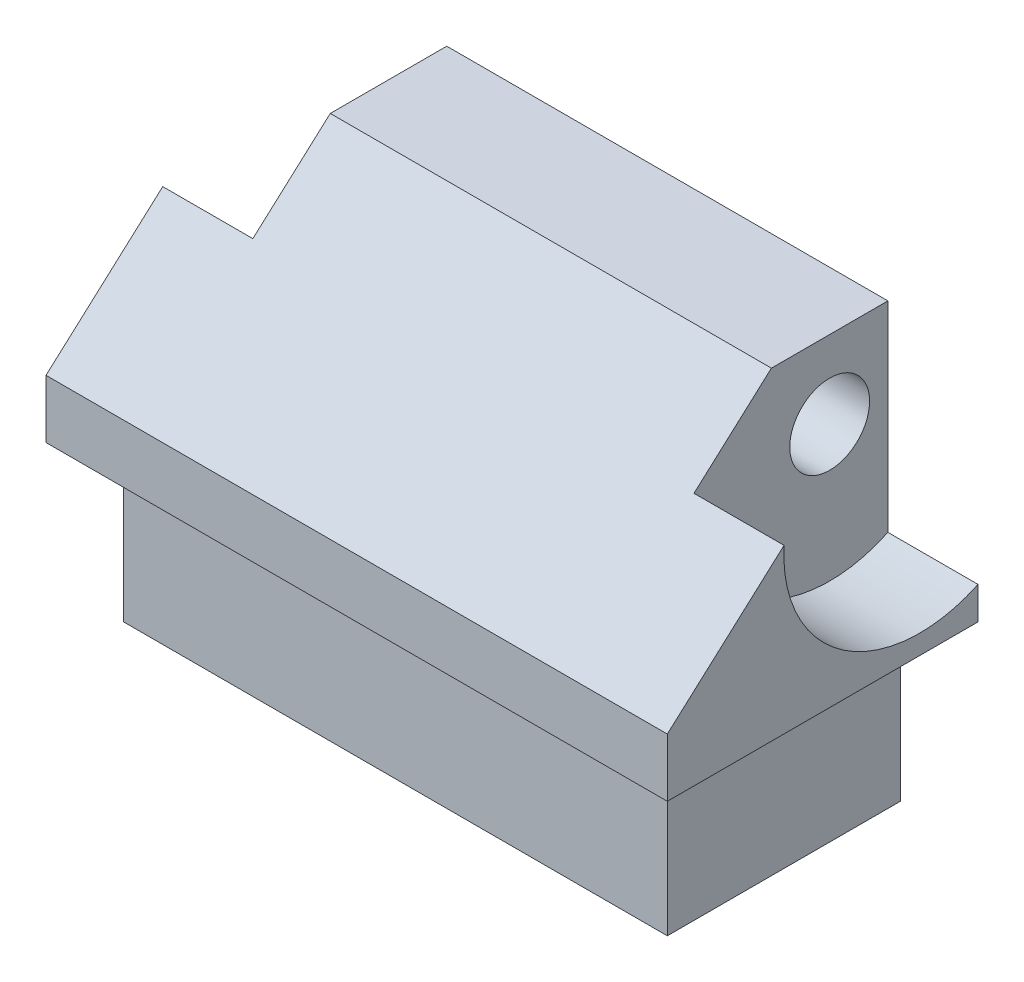
SolidWorks part; units mm, degrees
material "6061-T6 (SS)"
ref_plane "Front Plane" through (0, 0, 0) normal (0, 0, 1) x (1, 0, 0)
ref_plane "Top Plane" through (0, 0, 0) normal (0, 1, 0) x (1, 0, 0)
ref_plane "Right Plane" through (0, 0, 0) normal (1, 0, 0) x (0, 0, -1)
sketch "Sketch2" plane through (0, 0, 0) normal (0, 1, 0) x (1, 0, 0)
  line L1 (22.225, -9.525) -> (-22.225, -9.525)
  line L2 (22.225, -9.525) -> (22.225, 9.525)
  line L3 (22.225, 9.525) -> (-22.225, 9.525)
  line L4 (-22.225, -9.525) -> (-22.225, 9.525)
  line L5 (22.225, -9.525) -> (-22.225, 9.525) construction
  line L6 (22.225, 9.525) -> (-22.225, -9.525) construction
  point P0 (0, 0)
  dimension "D1" = 44.45
  dimension "D2" = 19.05
extrude "Boss-Extrude1" add sketch "Sketch2" against normal blind 12.7
sketch "Sketch3" plane through (0, 0, 0) normal (0, 1, 0) x (1, 0, 0)
  line L1 (25.4, 12.7) -> (-25.4, 12.7)
  line L2 (25.4, 12.7) -> (25.4, -12.7)
  line L3 (25.4, -12.7) -> (-25.4, -12.7)
  line L4 (-25.4, 12.7) -> (-25.4, -12.7)
  line L5 (25.4, 12.7) -> (-25.4, -12.7) construction
  line L6 (25.4, -12.7) -> (-25.4, 12.7) construction
  point P0 (0, 0)
  dimension "D1" = 25.4
  dimension "D2" = 50.8
extrude "Boss-Extrude2" add sketch "Sketch3" along normal blind 3.175
sketch "Sketch4" plane through (0, 0, 0) normal (1, 0, 0) x (0, 0, -1)
  line L0 (-12.7, 3.175) -> (-12.7, 4.7625)
  line L1 (3.175, 19.05) -> (12.7, 19.05)
  line L3 (12.7, 19.05) -> (12.7, 3.175)
  line L4 (12.7, 3.175) -> (-12.7, 3.175)
  line L5 (-12.7, 4.7625) -> (3.175, 19.05)
  point P3 (5.5481, 15.875)
  dimension "D1" = 1.5875
  dimension "D2" = 9.525
  dimension "D3" = 15.875
extrude "Boss-Extrude3" add sketch "Sketch4" along normal mid plane 50.8
sketch "Sketch5" plane through (25.4, 0, 0) normal (1, 0, 0) x (0, 0, -1)
  line L0 (7.9375, 12.7) -> (0, 12.7) construction
  line L1 (0, 12.7) -> (0, 0) construction
  line L2 (-9.525, 0) -> (9.525, 0) construction
  line L3 (19.05, 12.7) -> (12.7, 12.7) construction
  line L4 (12.7, 19.05) -> (12.7, 0) construction
  circle A0 centre (7.9375, 12.7) radius 11.1125
  dimension "D3" = 22.225
  dimension "D1" = 12.7
  dimension "D2" = 6.35
extrude "Cut-Extrude1" cut sketch "Sketch5" against normal blind 7.366
sketch "Sketch6" plane through (18.034, 0, 0) normal (1, 0, 0) x (0, 0, -1)
  circle A0 centre (7.9375, 12.7) radius 3.2639
  arc A1 (-3.1558, 13.3522) -> (12.7, 2.6598) centre (7.9375, 12.7) ccw construction
  dimension "D1" = 6.5278
extrude "Cut-Extrude2" cut sketch "Sketch6" against normal through all
mirror "Mirror1" about plane through (0, 0, 0) normal (1, 0, 0) of "Cut-Extrude1"
